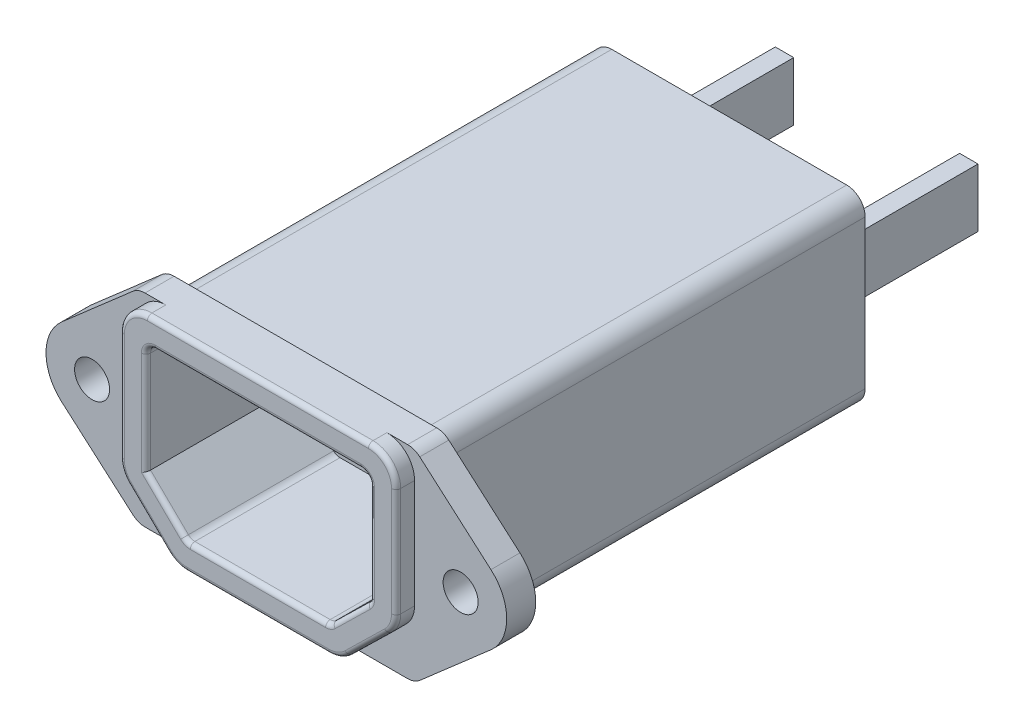
SolidWorks part; units mm, degrees
ref_plane "Front Plane" through (0, 0, 0) normal (0, 0, 1) x (1, 0, 0)
ref_plane "Top Plane" through (0, 0, 0) normal (0, 1, 0) x (1, 0, 0)
ref_plane "Right Plane" through (0, 0, 0) normal (1, 0, 0) x (0, 0, -1)
sketch "Sketch1" plane through (0, 0, 0) normal (0, 0, 1) x (1, 0, 0)
  line L0 (-20, 0) -> (20, 0) construction
  line L1 (-15.5651, 10.5068) -> (-23.2877, 3.7671)
  line L2 (7.3425, -8.15) -> (-7.3425, -8.15)
  line L3 (12.15, -3.429) -> (12.15, 7.15)
  line L4 (11.15, 8.15) -> (-11.15, 8.15)
  line L5 (-12.15, -3.85) -> (-12.15, 7.15)
  line L6 (12.15, -8.15) -> (-12.15, 8.15) construction
  line L7 (12.15, 8.15) -> (-12.15, -8.15) construction
  line L8 (14.25, -11) -> (-14.25, -11)
  line L9 (15, -11) -> (15, 11) construction
  line L10 (14.25, 11) -> (-14.25, 11)
  line L11 (-15, -11) -> (-15, 11) construction
  line L12 (15, -11) -> (-15, 11) construction
  line L13 (15, 11) -> (-15, -11) construction
  line L14 (0, 0) -> (0, -22.9416) construction
  line L15 (15.5651, 10.5068) -> (23.2877, 3.7671)
  line L16 (15.5651, -10.5068) -> (23.2877, -3.7671)
  line L17 (-15.5651, -10.5068) -> (-23.2877, -3.7671)
  line L18 (-8.0414, -7.8652) -> (-12.15, -3.85)
  line L19 (8.0414, -7.8652) -> (11.8489, -4.1442)
  line L20 (-12.15, -8.15) -> (-12.15, -3.85) construction
  line L21 (-12.15, -8.15) -> (-7.3425, -8.15) construction
  line L22 (7.3425, -8.15) -> (12.15, -8.15) construction
  line L23 (12.15, -8.15) -> (12.15, -3.429) construction
  line L24 (-12.15, 8.15) -> (-12.15, 7.15) construction
  line L25 (12.15, 7.15) -> (12.15, 8.15) construction
  line L26 (12.15, 8.15) -> (11.15, 8.15) construction
  circle A0 centre (-20, 0) radius 1.9
  circle A1 centre (20, 0) radius 1.9
  arc A2 (-23.2877, 3.7671) -> (-23.2877, -3.7671) centre (-20, 0) ccw
  arc A3 (23.2877, -3.7671) -> (23.2877, 3.7671) centre (20, 0) ccw
  arc A4 (-15, 0) -> (-23.2877, 3.7671) centre (-20, 0) ccw construction
  arc A5 (-23.2877, -3.7671) -> (-15, 0) centre (-20, 0) ccw construction
  arc A6 (15, 0) -> (23.2877, -3.7671) centre (20, 0) ccw construction
  arc A7 (23.2877, 3.7671) -> (15, 0) centre (20, 0) ccw construction
  arc A8 (-14.25, -11) -> (-15.5651, -10.5068) centre (-14.25, -9) cw
  arc A9 (14.25, -11) -> (15.5651, -10.5068) centre (14.25, -9) ccw
  arc A10 (15.5651, 10.5068) -> (14.25, 11) centre (14.25, 9) ccw
  arc A11 (-14.25, 11) -> (-15.5651, 10.5068) centre (-14.25, 9) ccw
  arc A12 (12.15, -3.429) -> (11.8489, -4.1442) centre (11.15, -3.429) cw
  arc A13 (7.3425, -8.15) -> (8.0414, -7.8652) centre (7.3425, -7.15) ccw
  arc A14 (-7.3425, -8.15) -> (-8.0414, -7.8652) centre (-7.3425, -7.15) cw
  arc A15 (12.15, 7.15) -> (11.15, 8.15) centre (11.15, 7.15) ccw
  arc A16 (-11.15, 8.15) -> (-12.15, 7.15) centre (-11.15, 7.15) ccw
  point P2 (0, 0)
  point P3 (0, 0)
  point P11 (0, 0)
  point P18 (-25, 0)
  point P19 (25, 0)
  point P42 (0, -8.15)
  point P55 (0, 0)
  dimension "D1" = 3.8
  dimension "D8" = 2
  dimension "D3" = 1
  dimension "D2" = 40
  dimension "D4" = 24.3
  dimension "D5" = 30
  dimension "D6" = 22
  dimension "D7" = 50
  dimension "D9" = 16.3
  dimension "D10" = 14.685
  dimension "D11" = 12
  dimension "D12" = 4.721
extrude "Boss-Extrude1" add sketch "Sketch1" along normal blind 3.15
sketch "Sketch2" plane through (0, 0, 3.15) normal (0, 0, 1) x (1, 0, 0)
  line L0 (15, -11) -> (15, 11) construction
  line L1 (-15, -11) -> (-15, 11) construction
  line L2 (-8.0414, -7.8652) -> (-12.15, -3.85) construction
  line L3 (7.3425, -8.15) -> (-7.3425, -8.15) construction
  line L4 (8.0414, -7.8652) -> (11.8489, -4.1442) construction
  line L5 (12.15, -3.429) -> (12.15, 7.15) construction
  line L6 (11.15, 8.15) -> (-11.15, 8.15) construction
  line L7 (-12.15, -3.85) -> (-12.15, 7.15) construction
  line L8 (15, -3.7869) -> (15, 8)
  line L9 (-15, -3.7869) -> (-15, 8)
  line L10 (-8.0414, -7.8652) -> (-12.15, -3.85)
  line L11 (7.3425, -8.15) -> (-7.3425, -8.15)
  line L12 (8.0414, -7.8652) -> (11.8489, -4.1442)
  line L13 (12.15, -3.429) -> (12.15, 7.15)
  line L14 (11.15, 8.15) -> (-11.15, 8.15)
  line L15 (-12.15, -3.85) -> (-12.15, 7.15)
  line L16 (-12, 11) -> (12, 11)
  line L17 (14.0968, -5.9324) -> (9.7857, -10.1456)
  line L18 (14.25, -11) -> (-14.25, -11) construction
  line L19 (7.6889, -11) -> (-7.6889, -11)
  line L20 (-9.7857, -10.1456) -> (-14.0968, -5.9324)
  line L21 (0, -11) -> (0, 0) construction
  line L22 (-15, -5.0497) -> (-12.15, -5.0497) construction
  line L23 (-10.0957, -5.8576) -> (-12.0877, -7.8959) construction
  line L24 (-15, -11) -> (-15, -5.0497) construction
  line L25 (15, -11) -> (15, -5.0497) construction
  arc A0 (-8.0414, -7.8652) -> (-7.3425, -8.15) centre (-7.3425, -7.15) ccw construction
  arc A1 (7.3425, -8.15) -> (8.0414, -7.8652) centre (7.3425, -7.15) ccw construction
  arc A2 (11.8489, -4.1442) -> (12.15, -3.429) centre (11.15, -3.429) ccw construction
  arc A3 (12.15, 7.15) -> (11.15, 8.15) centre (11.15, 7.15) ccw construction
  arc A4 (-11.15, 8.15) -> (-12.15, 7.15) centre (-11.15, 7.15) ccw construction
  arc A5 (-8.0414, -7.8652) -> (-7.3425, -8.15) centre (-7.3425, -7.15) ccw
  arc A6 (7.3425, -8.15) -> (8.0414, -7.8652) centre (7.3425, -7.15) ccw
  arc A7 (11.8489, -4.1442) -> (12.15, -3.429) centre (11.15, -3.429) ccw
  arc A8 (12.15, 7.15) -> (11.15, 8.15) centre (11.15, 7.15) ccw
  arc A9 (-11.15, 8.15) -> (-12.15, 7.15) centre (-11.15, 7.15) ccw
  arc A10 (9.7857, -10.1456) -> (7.6889, -11) centre (7.6889, -8) cw
  arc A11 (-7.6889, -11) -> (-9.7857, -10.1456) centre (-7.6889, -8) cw
  arc A12 (-14.0968, -5.9324) -> (-15, -3.7869) centre (-12, -3.7869) cw
  arc A13 (14.0968, -5.9324) -> (15, -3.7869) centre (12, -3.7869) ccw
  arc A14 (15, 8) -> (12, 11) centre (12, 8) ccw
  arc A15 (-15, 8) -> (-12, 11) centre (-12, 8) cw
  point P34 (8.9114, -11)
  point P37 (-8.9114, -11)
  dimension "D1" = 3
extrude "Boss-Extrude2" add sketch "Sketch2" along normal blind 2
fillet "Fillet1" radius 0.5 23 edges at (0, -8.15, 5.15) (7.7199, -8.0761, 5.15) (9.9452, -6.0047, 5.15) (12.0717, -3.817, 5.15) (12.15, 1.8605, 5.15) (11.8571, 7.8571, 5.15) (0, 8.15, 5.15) (-11.8571, 7.8571, 5.15) (-12.15, 1.65, 5.15) (-10.0957, -5.8576, 5.15) (-7.7199, -8.0761, 5.15) (0, -11, 5.15) (-8.821, -10.7782, 5.15) (-11.9412, -8.039, 5.15) (-14.765, -4.9508, 5.15) (-15, 2.1066, 5.15) (-14.1213, 10.1213, 5.15) (0, 11, 5.15) (14.1213, 10.1213, 5.15) (15, 2.1066, 5.15) (14.765, -4.9508, 5.15) (11.9412, -8.039, 5.15) (8.821, -10.7782, 5.15)
sketch "Sketch3" plane through (0, 0, 0) normal (0, 0, -1) x (-1, 0, 0)
  line L1 (12.75, -10.075) -> (-12.75, -10.075)
  line L2 (14.75, -8.075) -> (14.75, 8.075)
  line L3 (12.75, 10.075) -> (-12.75, 10.075)
  line L4 (-14.75, -8.075) -> (-14.75, 8.075)
  line L5 (14.75, -10.075) -> (-14.75, 10.075) construction
  line L6 (14.75, 10.075) -> (-14.75, -10.075) construction
  arc A0 (-12.75, -10.075) -> (-14.75, -8.075) centre (-12.75, -8.075) cw
  arc A1 (12.75, -10.075) -> (14.75, -8.075) centre (12.75, -8.075) ccw
  arc A2 (14.75, 8.075) -> (12.75, 10.075) centre (12.75, 8.075) ccw
  arc A3 (-12.75, 10.075) -> (-14.75, 8.075) centre (-12.75, 8.075) ccw
  point P0 (0, 0)
  dimension "D3" = 2
  dimension "D1" = 20.15
  dimension "D2" = 29.5
extrude "Boss-Extrude3" add sketch "Sketch3" along normal blind 46
sketch "Sketch4" plane through (0, 0, -46) normal (0, 0, -1) x (-1, 0, 0)
  line L0 (0, 0) -> (-10, 0) construction
  line L1 (0, 0) -> (0, 6.3206) construction
  line L2 (-11, -3.175) -> (-9, -3.175)
  line L3 (-11, -3.175) -> (-11, 3.175)
  line L4 (-11, 3.175) -> (-9, 3.175)
  line L5 (-9, -3.175) -> (-9, 3.175)
  line L6 (-11, -3.175) -> (-9, 3.175) construction
  line L7 (-11, 3.175) -> (-9, -3.175) construction
  line L8 (11, 3.175) -> (9, 3.175)
  line L9 (9, -3.175) -> (9, 3.175)
  line L10 (11, -3.175) -> (9, -3.175)
  line L11 (11, -3.175) -> (11, 3.175)
  dimension "D1" = 6.35
  dimension "D2" = 2
  dimension "D3" = 20
extrude "Boss-Extrude4" add sketch "Sketch4" along normal blind 16
sketch "Sketch5" plane through (0, 0, 0) normal (0, 0, 1) x (1, 0, 0)
  line L6 (-12.15, 7.15) -> (-12.15, -3.85)
  line L7 (-12.15, -3.85) -> (-8.0414, -7.8652)
  line L8 (-7.3425, -8.15) -> (7.3425, -8.15)
  line L9 (8.0414, -7.8652) -> (11.8489, -4.1442)
  line L10 (12.15, -3.429) -> (12.15, 7.15)
  line L11 (11.15, 8.15) -> (-11.15, 8.15)
  line L12 (-12.15, 7.15) -> (-12.15, -3.85)
  line L13 (-12.15, -3.85) -> (-8.0414, -7.8652)
  line L14 (-7.3425, -8.15) -> (7.3425, -8.15)
  line L15 (8.0414, -7.8652) -> (11.8489, -4.1442)
  line L16 (12.15, -3.429) -> (12.15, 7.15)
  line L17 (11.15, 8.15) -> (-11.15, 8.15)
  arc A5 (-8.0414, -7.8652) -> (-7.3425, -8.15) centre (-7.3425, -7.15) ccw
  arc A6 (7.3425, -8.15) -> (8.0414, -7.8652) centre (7.3425, -7.15) ccw
  arc A7 (11.8489, -4.1442) -> (12.15, -3.429) centre (11.15, -3.429) ccw
  arc A8 (12.15, 7.15) -> (11.15, 8.15) centre (11.15, 7.15) ccw
  arc A9 (-11.15, 8.15) -> (-12.15, 7.15) centre (-11.15, 7.15) ccw
  arc A10 (-8.0414, -7.8652) -> (-7.3425, -8.15) centre (-7.3425, -7.15) ccw
  arc A11 (7.3425, -8.15) -> (8.0414, -7.8652) centre (7.3425, -7.15) ccw
  arc A12 (11.8489, -4.1442) -> (12.15, -3.429) centre (11.15, -3.429) ccw
  arc A13 (12.15, 7.15) -> (11.15, 8.15) centre (11.15, 7.15) ccw
  arc A14 (-11.15, 8.15) -> (-12.15, 7.15) centre (-11.15, 7.15) ccw
  dimension "D1" = 0
extrude "Cut-Extrude1" cut sketch "Sketch5" against normal blind 11.1
